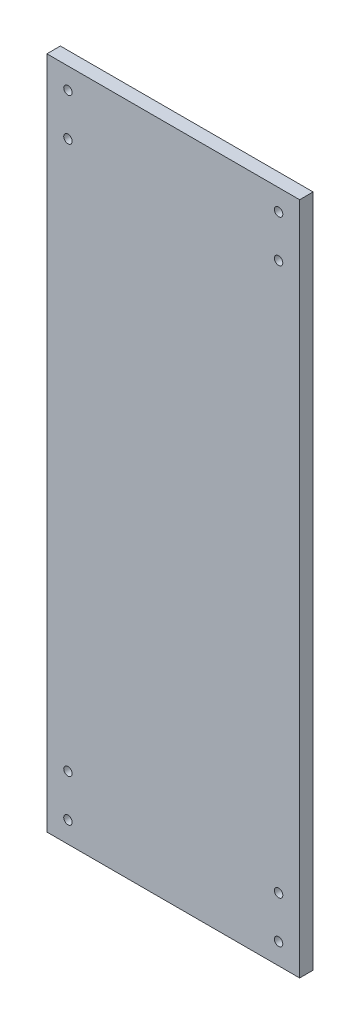
SolidWorks part; units mm, degrees
ref_plane "Front Plane" through (0, 0, 0) normal (0, 0, 1) x (1, 0, 0)
ref_plane "Top Plane" through (0, 0, 0) normal (0, 1, 0) x (1, 0, 0)
ref_plane "Right Plane" through (0, 0, 0) normal (1, 0, 0) x (0, 0, -1)
sketch "Model" plane through (0, 0, 0) normal (0, 0, 1) x (1, 0, 0)
  line L0 (142.0962, -1) -> (112.0962, -1)
  line L1 (112.0962, -1) -> (112.0962, 79)
  line L2 (112.0962, 79) -> (142.0962, 79)
  line L3 (142.0962, 79) -> (142.0962, -1)
  circle A0 centre (114.5962, 6.5) radius 0.5
  circle A1 centre (114.5962, 71.5) radius 0.5
  circle A2 centre (139.5962, 6.5) radius 0.5
  circle A3 centre (139.5962, 71.5) radius 0.5
  circle A4 centre (114.5962, 76.5) radius 0.5
  circle A5 centre (139.5962, 76.5) radius 0.5
  circle A6 centre (114.5962, 1.5) radius 0.5
  circle A7 centre (139.5962, 1.5) radius 0.5
extrude "Boss-Extrude1" add sketch "Model" along normal blind 1.6
